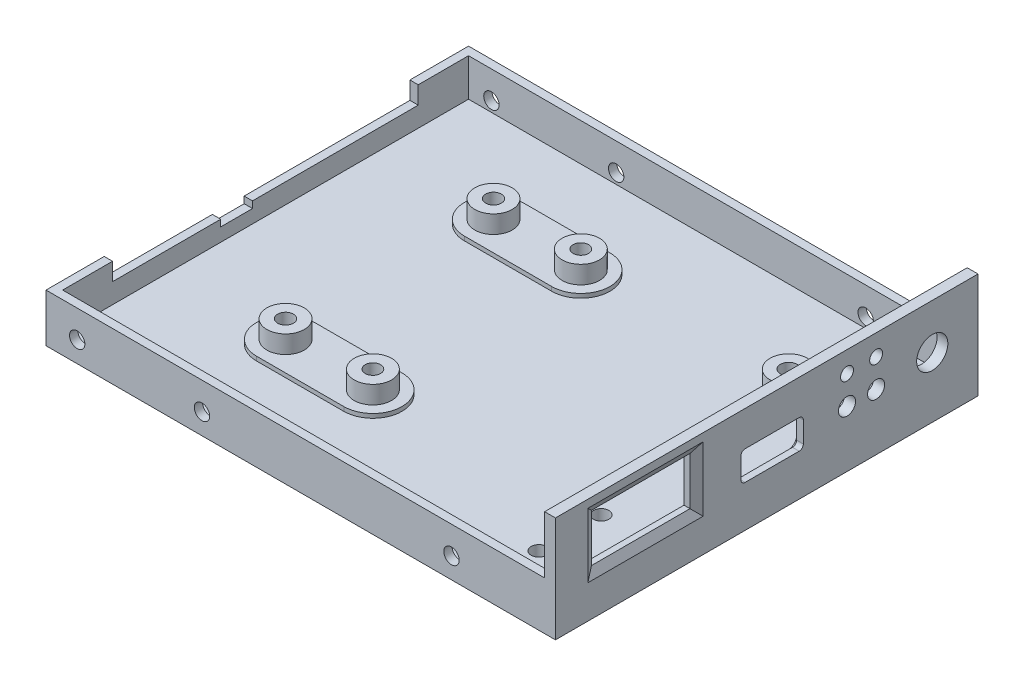
SolidWorks part; units mm, degrees
ref_plane "前视基准面" through (0, 0, 0) normal (0, 0, 1) x (1, 0, 0)
ref_plane "上视基准面" through (0, 0, 0) normal (0, 1, 0) x (1, 0, 0)
ref_plane "右视基准面" through (0, 0, 0) normal (1, 0, 0) x (0, 0, -1)
other "Configuration Table"
sketch "草图1" plane through (0, 0, 0) normal (0, 1, 0) x (1, 0, 0)
  line L1 (-79.9533, 37.1835) -> (42.5467, 37.1835)
  line L2 (-79.9533, 37.1835) -> (-79.9533, -64.4165)
  line L3 (-79.9533, -64.4165) -> (42.5467, -64.4165)
  line L4 (42.5467, 37.1835) -> (42.5467, -64.4165)
  dimension "D1" = 101.6
  dimension "D2" = 122.5
extrude "凸台-拉伸1" add sketch "草图1" along normal blind 25.4
sketch "草图2" plane through (0, 25.4, 0) normal (0, 1, 0) x (1, 0, 0)
  line L0 (42.5467, 37.1835) -> (-79.9533, 37.1835) construction
  line L1 (-77.9533, 35.1835) -> (39.9467, 35.1835)
  line L2 (-77.9533, 35.1835) -> (-77.9533, -62.4165)
  line L3 (-77.9533, -62.4165) -> (39.9467, -62.4165)
  line L4 (39.9467, 35.1835) -> (39.9467, -62.4165)
  line L5 (-79.9533, -64.4165) -> (42.5467, -64.4165) construction
  line L6 (-79.9533, 37.1835) -> (-79.9533, -64.4165) construction
  line L7 (42.5467, -64.4165) -> (42.5467, 37.1835) construction
  dimension "D1" = 2
  dimension "D2" = 2
  dimension "D3" = 2
  dimension "D4" = 2.6
extrude "切除-拉伸1" cut sketch "草图2" along direction (0, 1, 0) on the side against the normal offset from surface (22.857 mm away) 2.543
sketch "草图5" plane through (0, 0, -37.1835) normal (0, 0, -1) x (-1, 0, 0)
  line L0 (-42.5467, 25.4) -> (-42.5467, 0) construction
  line L1 (79.9533, 25.4) -> (-39.9467, 25.4)
  line L2 (79.9533, 25.4) -> (79.9533, 11.6)
  line L3 (79.9533, 11.6) -> (-39.9467, 11.6)
  line L4 (-39.9467, 25.4) -> (-39.9467, 11.6)
  line L5 (-42.5467, 0) -> (79.9533, 0) construction
  dimension "D1" = 2.6
  dimension "D2" = 11.6
extrude "切除-拉伸2" cut sketch "草图5" against normal up to next
sketch "草图6" plane through (-79.9533, 0, 0) normal (-1, 0, 0) x (0, 0, 1)
  line L0 (64.4165, 11.6) -> (-37.1835, 11.6) construction
  line L1 (-23.0835, 11.6) -> (50.4165, 11.6)
  line L2 (-23.0835, 11.6) -> (-23.0835, 7.35)
  line L3 (-23.0835, 7.35) -> (50.4165, 7.35)
  line L4 (50.4165, 11.6) -> (50.4165, 7.35)
  line L5 (-37.1835, 0) -> (64.4165, 0) construction
  line L6 (-37.1835, 11.6) -> (-37.1835, 0) construction
  dimension "D1" = 7.35
  dimension "D2" = 73.5
  dimension "D3" = 14.1
extrude "切除-拉伸3" cut sketch "草图6" against normal up to next
sketch "草图7" plane through (-79.9533, 0, 0) normal (-1, 0, 0) x (0, 0, 1)
  line L0 (-23.0835, 7.35) -> (50.4165, 7.35) construction
  line L1 (16.7665, 7.35) -> (24.4165, 7.35)
  line L2 (16.7665, 7.35) -> (16.7665, 5.75)
  line L3 (16.7665, 5.75) -> (24.4165, 5.75)
  line L4 (24.4165, 7.35) -> (24.4165, 5.75)
  line L5 (50.4165, 7.35) -> (50.4165, 11.6) construction
  dimension "D1" = 7.65
  dimension "D2" = 1.6
  dimension "D3" = 26
extrude "切除-拉伸4" cut sketch "草图7" against normal up to next
sketch "草图8" plane through (0, 0, 64.4165) normal (0, 0, 1) x (1, 0, 0)
  line L0 (-79.9533, 11.6) -> (-79.9533, 0) construction
  line L1 (-79.9533, 0) -> (42.5467, 0) construction
  line L2 (17.5467, 5) -> (-42.4533, 5) construction
  line L3 (-42.4533, 5) -> (-72.4533, 5) construction
  circle A0 centre (17.5467, 5) radius 1.85
  circle A1 centre (-42.4533, 5) radius 1.85
  circle A2 centre (-72.4533, 5) radius 1.85
  dimension "D1" = 3.7
  dimension "D2" = 97.5
  dimension "D3" = 5
  dimension "D6" = 60
  dimension "D7" = 30
  dimension "D4" = 2
  dimension "D5" = 2
extrude "切除-拉伸5" cut sketch "草图8" against normal up to next
sketch "草图9" plane through (0, 2.543, 0) normal (0, 1, 0) x (1, 0, 0)
  line L0 (39.9467, -13.6165) -> (-86.6151, -13.6165) construction
  line L1 (39.9467, 35.1835) -> (39.9467, -62.4165) construction
ref_plane "基准面1" through (0, 0, 13.6165) normal (0, 0, 1) x (1, 0, 0)
mirror "镜向1" about plane through (0, 0, 13.6165) normal (0, 0, 1) of "切除-拉伸5"
sketch "草图10" plane through (0, 2.543, 0) normal (0, 1, 0) x (1, 0, 0)
  line L0 (-48.9533, 12.1835) -> (-27.9533, 12.1835) construction
  line L1 (-48.9533, 19.1835) -> (-27.9533, 19.1835)
  line L2 (-48.9533, 5.1835) -> (-27.9533, 5.1835)
  line L3 (-77.9533, 35.1835) -> (39.9467, 35.1835) construction
  line L4 (-77.9533, -62.4165) -> (-77.9533, 35.1835) construction
  arc A0 (-48.9533, 19.1835) -> (-48.9533, 5.1835) centre (-48.9533, 12.1835) ccw
  arc A1 (-27.9533, 5.1835) -> (-27.9533, 19.1835) centre (-27.9533, 12.1835) ccw
  point P2 (-38.4533, 12.1835)
  dimension "D1" = 14
  dimension "D2" = 21
  dimension "D3" = 23
  dimension "D4" = 29
extrude "凸台-拉伸2" add sketch "草图10" along normal blind 1
sketch "草图11" plane through (0, 3.543, 0) normal (0, 1, 0) x (1, 0, 0)
  circle A0 centre (-48.9533, 12.1835) radius 4.5
  circle A1 centre (-27.9533, 12.1835) radius 4.5
  dimension "D1" = 9
  dimension "D2" = 9
extrude "凸台-拉伸3" add sketch "草图11" along normal blind 4.3
sketch "草图12" plane through (0, 7.843, 0) normal (0, 1, 0) x (1, 0, 0)
  circle A0 centre (-48.9533, 12.1835) radius 1.9
  dimension "D1" = 3.8
sketch "草图13" plane through (0, 7.843, 0) normal (0, 1, 0) x (1, 0, 0)
  circle A0 centre (-27.9533, 12.1835) radius 1.85
  dimension "D1" = 3.7
extrude "切除-拉伸6" cut sketch "草图13" against normal up to next
sketch "草图14" plane through (0, 2.543, 0) normal (0, 1, 0) x (1, 0, 0)
  line L0 (-48.9533, 5.1835) -> (-27.9533, 5.1835) construction
  circle A0 centre (22.0467, 12.1835) radius 4.5
  circle A1 centre (-27.9533, 12.1835) radius 4.5 construction
  circle A2 centre (22.0467, 12.1835) radius 2
  dimension "D1" = 9
  dimension "D2" = 50
  dimension "D3" = 7
  dimension "D4" = 4
extrude "凸台-拉伸5" add sketch "草图14" along normal blind 5.3
sketch "草图15" plane through (42.5467, 0, 0) normal (1, 0, 0) x (0, 0, -1)
  line L0 (-64.4165, 0) -> (37.1835, 0) construction
  line L1 (37.1835, 25.4) -> (37.1835, 0) construction
  circle A0 centre (12.6835, 20.4) radius 1.55
  circle A1 centre (12.6835, 13.6) radius 2.05
  circle A2 centre (5.6835, 20.4) radius 1.55
  circle A3 centre (5.6835, 13.6) radius 2.05
  dimension "D1" = 3.1
  dimension "D2" = 4.1
  dimension "D3" = 6.8
  dimension "D4" = 13.6
  dimension "D5" = 24.5
  dimension "D6" = 24.5
  dimension "D8" = 7
  dimension "D7" = 2
extrude "切除-拉伸7" cut sketch "草图15" against normal blind 5.3
sketch "草图16" plane through (42.5467, 0, 0) normal (1, 0, 0) x (0, 0, -1)
  line L0 (37.1835, 25.4) -> (37.1835, 0) construction
  line L1 (-19.8165, 17) -> (-4.8165, 17)
  line L2 (-19.8165, 17) -> (-19.8165, 10)
  line L3 (-19.8165, 10) -> (-4.8165, 10)
  line L4 (-4.8165, 17) -> (-4.8165, 10)
  line L5 (-64.4165, 0) -> (37.1835, 0) construction
  dimension "D1" = 7
  dimension "D2" = 15
  dimension "D3" = 42
  dimension "D4" = 10
extrude "切除-拉伸8" cut sketch "草图16" against normal blind 5.3
fillet "圆角1" radius 1 4 edges at (41.2467, 10, 4.8165) (41.2467, 10, 19.8165) (41.2467, 17, 4.8165) (41.2467, 17, 19.8165)
sketch "草图17" plane through (42.5467, 0, 0) normal (1, 0, 0) x (0, 0, -1)
  line L0 (-64.4165, 0) -> (37.1835, 0) construction
  line L1 (-54.6165, 21.5) -> (-30.9165, 21.5)
  line L2 (-54.6165, 21.5) -> (-54.6165, 10)
  line L3 (-54.6165, 10) -> (-30.9165, 10)
  line L4 (-30.9165, 21.5) -> (-30.9165, 10)
  line L5 (-64.4165, 25.4) -> (-64.4165, 0) construction
  dimension "D1" = 23.7
  dimension "D2" = 11.5
  dimension "D3" = 33.5
  dimension "D4" = 10
extrude "切除-拉伸9" cut sketch "草图17" against normal blind 5.3
chamfer "倒角2" distance 2 angle 30 4 edges at (42.5467, 10, 42.7665) (42.5467, 15.75, 30.9165) (42.5467, 21.5, 42.7665) (42.5467, 15.75, 54.6165)
extrude "切除-拉伸10" cut sketch "草图12" against normal up to surface (7.843 mm away) up to face at (-27.9533, 0, -10.3335)
sketch "草图18" plane through (0, 2.543, 0) normal (0, 1, 0) x (1, 0, 0)
  circle A0 centre (22.0467, 12.1835) radius 2
extrude "切除-拉伸11" cut sketch "草图18" against normal up to surface (2.543 mm away) up to face at (-48.9533, 0, -10.2835)
sketch "草图19" plane through (39.9467, 0, 0) normal (-1, 0, 0) x (0, 0, 1)
  line L0 (-35.1835, 2.543) -> (62.4165, 2.543) construction
  line L1 (-35.1835, 2.543) -> (-35.1835, 11.6) construction
  circle A0 centre (-26.1835, 14.543) radius 3.75
  dimension "D1" = 7.5
  dimension "D2" = 12
  dimension "D3" = 9
extrude "切除-拉伸12" cut sketch "草图19" against normal blind 10
pattern_linear "阵列(线性)1" count 2 spacing 50 along (0, 0, 1) of "凸台-拉伸2", "凸台-拉伸3", "切除-拉伸6", "切除-拉伸10"
sketch "草图22" plane through (0, 2.543, 0) normal (0, 1, 0) x (1, 0, 0)
  line L0 (37.4467, -59.9165) -> (39.9467, -59.9165)
  line L9 (39.9467, -22.4165) -> (39.9467, -59.9165)
  line L12 (39.9467, -22.4165) -> (37.4467, -22.4165)
  line L13 (37.4467, -59.9165) -> (37.4467, -22.4165)
  dimension "D1" = 37.5
  dimension "D2" = 2.5
sketch "草图29" plane through (0, 2.543, 0) normal (0, 1, 0) x (1, 0, 0)
  line L0 (39.9467, 35.1835) -> (39.9467, -62.4165) construction
  line L5 (17.0467, -12.8165) -> (27.0467, -20.8165) construction
  line L6 (17.0467, -22.8165) -> (27.0467, -12.8165) construction
  circle A1 centre (22.0467, -16.8165) radius 1.35
  circle A2 centre (22.0467, 12.1835) radius 2 construction
  point P0 (22.0467, -16.8165)
  dimension "D1" = 29
  dimension "D2" = 17.9
  dimension "D3" = 10
  dimension "D5" = 2.7
  dimension "D4" = 10
sketch "草图30" plane through (0, 2.543, 0) normal (0, 1, 0) x (1, 0, 0)
  line L0 (-79.9533, -64.4165) -> (39.9467, -64.4165) construction
  line L1 (42.5467, -64.4165) -> (42.5467, 37.1835) construction
  circle A0 centre (24.5467, -50.4165) radius 1.85
  circle A1 centre (24.5467, -35.4165) radius 1.85
  dimension "D1" = 3.7
  dimension "D2" = 14
  dimension "D3" = 18
  dimension "D5" = 15
  dimension "D4" = 2
extrude "切除-拉伸17" cut sketch "草图30" against normal blind 10
chamfer "倒角3" distance 1 angle 45 8 edges at (39.9467, 10, 12.3165) (39.9467, 10.2929, 5.1094) (39.9467, 10.2929, 19.5236) (39.9467, 13.5, 4.8165) (39.9467, 13.5, 19.8165) (39.9467, 16.7071, 5.1094) (39.9467, 16.7071, 19.5236) (39.9467, 17, 12.3165)
